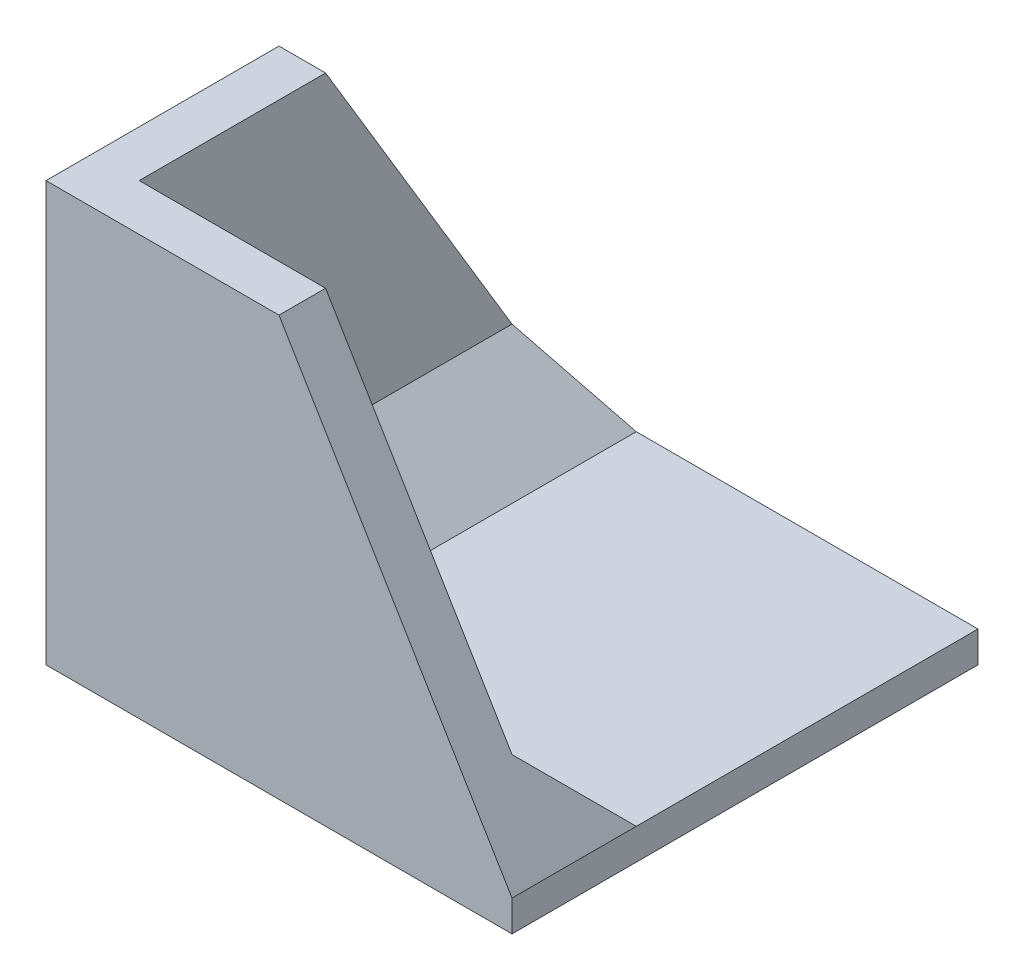
SolidWorks part; units mm, degrees
ref_plane "Front Plane" through (0, 0, 0) normal (0, 0, 1) x (1, 0, 0)
ref_plane "Top Plane" through (0, 0, 0) normal (0, 1, 0) x (1, 0, 0)
ref_plane "Right Plane" through (0, 0, 0) normal (1, 0, 0) x (0, 0, -1)
sketch "Sketch1" plane through (0, 0, 0) normal (0, 1, 0) x (1, 0, 0)
  line L1 (-19.05, -19.05) -> (19.05, -19.05)
  line L2 (-19.05, -19.05) -> (-19.05, 19.05)
  line L3 (-19.05, 19.05) -> (19.05, 19.05)
  line L4 (19.05, -19.05) -> (19.05, 19.05)
  line L5 (-19.05, -19.05) -> (19.05, 19.05) construction
  line L6 (-19.05, 19.05) -> (19.05, -19.05) construction
  point P0 (0, 0)
  dimension "D1" = 38.1
  dimension "D2" = 38.1
extrude "Boss-Extrude1" add sketch "Sketch1" along normal blind 2.54
sketch "Sketch2" plane through (0, 2.54, 0) normal (0, 1, 0) x (1, 0, 0)
  line L1 (0, 0) -> (-19.05, 0)
  line L2 (0, 0) -> (0, -19.05)
  line L3 (0, -19.05) -> (-19.05, -19.05)
  line L4 (-19.05, 0) -> (-19.05, -19.05)
extrude "Boss-Extrude2" add sketch "Sketch2" along normal blind 31.75
sketch "Sketch3" plane through (0, 0, 19.05) normal (0, 0, 1) x (1, 0, 0)
  line L0 (0, 34.29) -> (19.05, 2.54)
  line L1 (19.05, 2.54) -> (0, 2.54)
  line L2 (0, 2.54) -> (0, 34.29)
extrude "Boss-Extrude3" add sketch "Sketch3" against normal blind 3.81
sketch "Sketch4" plane through (-19.05, 0, 0) normal (-1, 0, 0) x (0, 0, 1)
  line L0 (0, 34.29) -> (0, 2.54)
  line L1 (0, 2.54) -> (-19.05, 2.54)
  line L2 (-19.05, 2.54) -> (0, 34.29)
extrude "Boss-Extrude4" add sketch "Sketch4" against normal blind 3.81
sketch "Sketch5" plane through (0, 34.29, 0) normal (0, 1, 0) x (1, 0, 0)
  line L1 (-15.24, 0) -> (0, 0)
  line L2 (-15.24, 0) -> (-15.24, -15.24)
  line L3 (-15.24, -15.24) -> (0, -15.24)
  line L4 (0, 0) -> (0, -15.24)
extrude "Cut-Extrude1" cut sketch "Sketch5" against normal up to surface (31.75 mm away) up to face at (1.27, 2.54, -1.27)
chamfer "Chamfer5" distance 6.35 angle 45 2 edges at (-15.24, 2.54, -1.905) (1.905, 2.54, 15.24)
